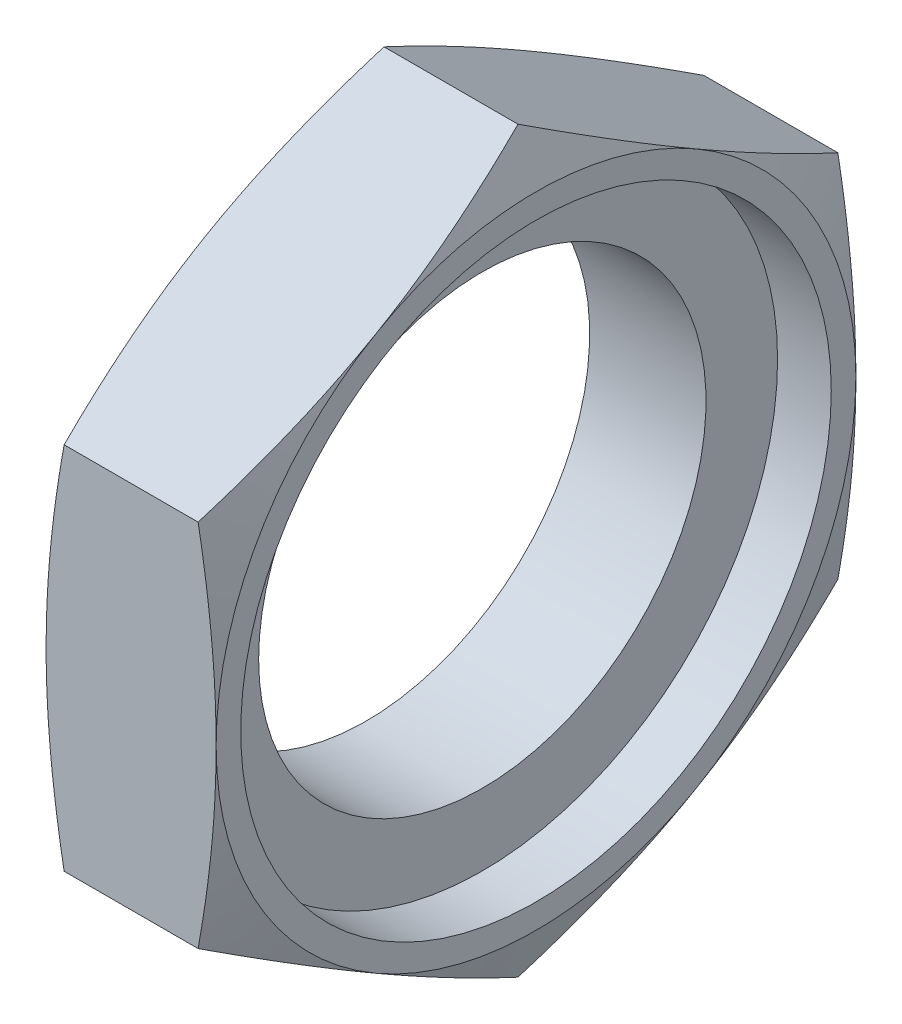
SolidWorks part; units mm, degrees
material "AISI 1020"
ref_plane "Plano superior" through (0, 0, 0) normal (0, 0, 1) x (1, 0, 0)
ref_plane "Plano frontal" through (0, 0, 0) normal (0, 1, 0) x (1, 0, 0)
ref_plane "Plano direito" through (0, 0, 0) normal (1, 0, 0) x (0, 0, -1)
sketch "Esboço1" plane through (0, 0, 0) normal (1, 0, 0) x (0, 0, -1)
  line L1 (14.3, 8.2561) -> (0, 16.5122)
  line L2 (0, 16.5122) -> (-14.3, 8.2561)
  line L3 (-14.3, 8.2561) -> (-14.3, -8.2561)
  line L4 (-14.3, -8.2561) -> (0, -16.5122)
  line L5 (0, -16.5122) -> (14.3, -8.2561)
  line L6 (14.3, -8.2561) -> (14.3, 8.2561)
  circle A0 centre (0, 0) radius 14.3 construction
  circle A1 centre (0, 0) radius 10
  dimension "D1" = 28.6
  dimension "D2" = 20
extrude "Ressalto-extrusão1" add sketch "Esboço1" along normal blind 7.6
cosmetic thread "Representação de rosca2" parameters "D2"=22
sketch "Esboço3" plane through (0, 0, 0) normal (-1, 0, 0) x (0, 0, 1)
  circle A0 centre (0, 0) radius 14.3
sketch "Esboço4" plane through (7.6, 0, 0) normal (1, 0, 0) x (0, 0, -1)
  circle A0 centre (0, 0) radius 14.3
hole_wizard "Furo1" positions "Esboço5" profile "Esboço6" legacy
sketch "Esboço5" plane through (7.6, 0, 0) normal (1, 0, 0) x (0, 0, -1)
  point P0 (0, 0)
  point P3 (0, 0)
sketch "Esboço6" plane through (7.6, 0, 0) normal (0, 1, 0) x (0, 0, -1)
  line L0 (0, 0) -> (0, 2.4)
  line L1 (0, 2.4) -> (13.2, 2.4)
  line L2 (13.2, 2.4) -> (13.2, 0)
  line L3 (13.2, 0) -> (0, 0)
  line L4 (0, 110) -> (0, -10) construction
  dimension "Diameter" = 26.4
  dimension "Depth" = 2.4
sketch "Esboço7" plane through (7.6, 0, 0) normal (1, 0, 0) x (0, 0, -1)
  circle A0 centre (0, 0) radius 14.3
extrude "Corte-extrusão1" cut sketch "Esboço7" against normal blind 13 draft 70 flip side to cut
sketch "Esboço8" plane through (0, 0, 0) normal (-1, 0, 0) x (0, 0, 1)
  circle A0 centre (0, 0) radius 14.3
extrude "Corte-extrusão2" cut sketch "Esboço8" against normal blind 13 draft 70 flip side to cut
